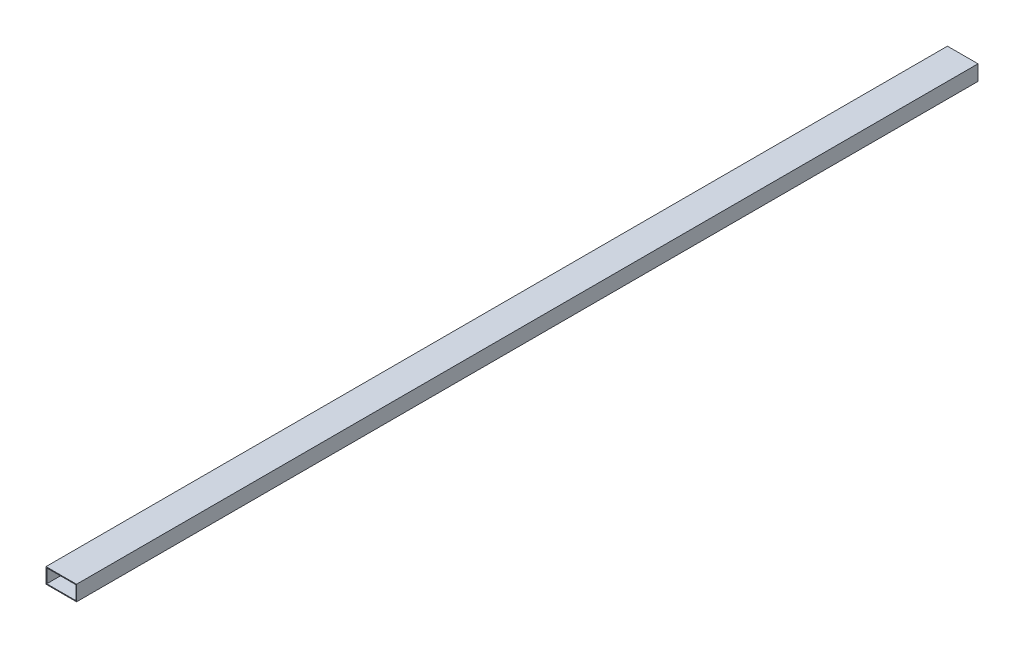
SolidWorks part; units mm, degrees
material "1100-H26 棒材(SS)"
ref_plane "前视基准面" through (0, 0, 0) normal (0, 0, 1) x (1, 0, 0)
ref_plane "上视基准面" through (0, 0, 0) normal (0, 1, 0) x (1, 0, 0)
ref_plane "右视基准面" through (0, 0, 0) normal (1, 0, 0) x (0, 0, -1)
other "Configuration Table"
sketch "草图1" plane through (0, 0, 0) normal (0, 0, 1) x (1, 0, 0)
  line L1 (0, 0) -> (40, 0)
  line L2 (0, 0) -> (0, 20)
  line L3 (0, 20) -> (40, 20)
  line L4 (40, 0) -> (40, 20)
  line L5 (1, 1) -> (39, 1)
  line L6 (1, 1) -> (1, 19)
  line L7 (1, 19) -> (39, 19)
  line L8 (39, 1) -> (39, 19)
  dimension "D1" = 40
  dimension "D2" = 20
  dimension "D3" = 1
  dimension "D4" = 1
  dimension "D5" = 1
  dimension "D6" = 1
extrude "凸台-拉伸1" add sketch "草图1" along normal blind 1180
